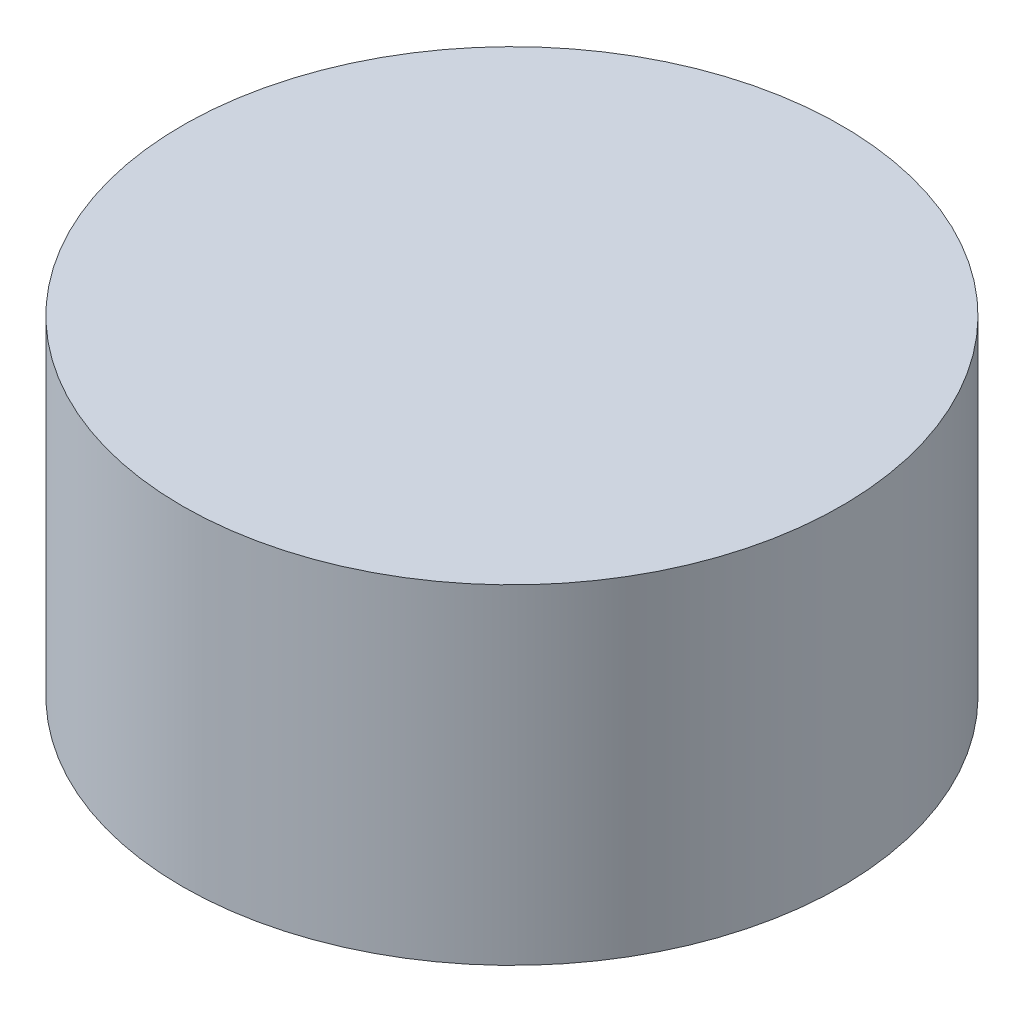
SolidWorks part; units mm, degrees
material "Balsa"
ref_plane "Front Plane" through (0, 0, 0) normal (0, 0, 1) x (1, 0, 0)
ref_plane "Top Plane" through (0, 0, 0) normal (0, 1, 0) x (1, 0, 0)
ref_plane "Right Plane" through (0, 0, 0) normal (1, 0, 0) x (0, 0, -1)
sketch "Sketch1" plane through (0, 0, 0) normal (0, 1, 0) x (1, 0, 0)
  circle A1 centre (0, 0) radius 12
  dimension "D2" = 12
extrude "Boss-Extrude1" add sketch "Sketch1" along normal blind 12
equation "\"Ring inner radius\"= 80mm"
equation "\"Heart cable hole radius\"= 3.5mm"
equation "\"Dogbone radius\"= 3mm"
equation "\"Tree side stock thickness\"= 6.7mm"
equation "\"Ring stock thickness\"= 6.7mm"
equation "\"D1@Boss-Extrude1\"= \"BottomRing Tab thickness\""
equation "\"Tree teeth\"= 15mm"
equation "\"Tree slot\"= 15mm"
equation "\"Bottom ring outer radius\"= \"Ring inner radius\" + \"Tree teeth\""
equation "\"Cut-Extrude Tolerance\"= 1mm"
equation "\"Ring outer radius\"= \"Ring inner radius\" + \"Tree slot\" + 10"
equation "\"Tree bottom teeth\"= 20mm"
equation "\"Top-bottom rings offset\"= 80mm"
equation "\"BottomRing layers overlap\"= 10mm"
equation "\"BottomRing inner radius\"= \"Ring inner radius\" - \"Tree teeth\" + \"Top-bottom rings offset\" + 20"
equation "\"BottomRing outer radius\"= \"BottomRing inner radius\" + \"BottomRing inner slot\" + \"BottomRing outer slot\" + \"BottomRing intersection\""
equation "\"BottomRing inner slot\"= 30mm"
equation "\"BottomRing outer slot\"= 40mm"
equation "\"BottomRing intersection\"= 60mm"
equation "\"BottomRing intersection with dogbones\"= \"BottomRing intersection\" - 2 * \"Dogbone radius\""
equation "\"BottomRing Tab radius\"= 12mm"
equation "\"BottomRing Tab thickness\"= 12mm"
equation "\"D2@Sketch1\"= \"BottomRing Tab radius\""
